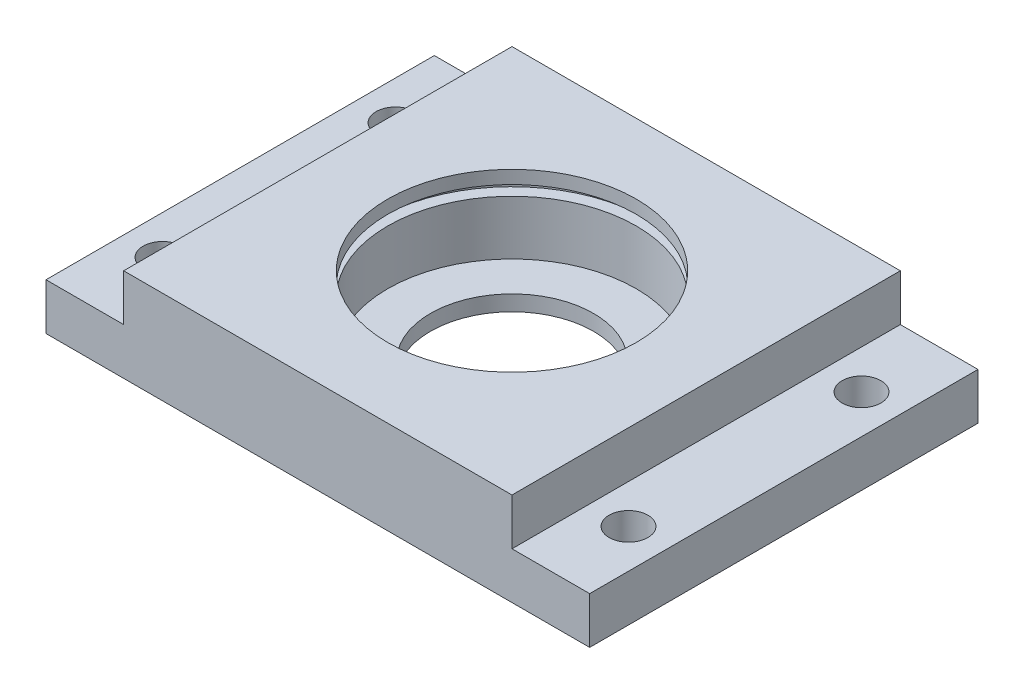
SolidWorks part; units mm, degrees
ref_plane "Front Plane" through (0, 0, 0) normal (0, 0, 1) x (1, 0, 0)
ref_plane "Top Plane" through (0, 0, 0) normal (0, 1, 0) x (1, 0, 0)
ref_plane "Right Plane" through (0, 0, 0) normal (1, 0, 0) x (0, 0, -1)
sketch "Sketch1" plane through (0, 0, 0) normal (0, 1, 0) x (1, 0, 0)
  line L1 (25, 25) -> (-25, 25)
  line L2 (25, 25) -> (25, -25)
  line L3 (25, -25) -> (-25, -25)
  line L4 (-25, 25) -> (-25, -25)
  line L5 (25, 25) -> (-25, -25) construction
  line L6 (25, -25) -> (-25, 25) construction
extrude "Boss-Extrude2" add sketch "Sketch1" along normal blind 12
sketch "Sketch3" plane through (0, 12, 0) normal (0, 1, 0) x (1, 0, 0)
  circle A0 centre (0, 0) radius 16
extrude "Cut-Extrude1" cut sketch "Sketch3" against normal blind 10
sketch "Sketch5" plane through (0, 0, 0) normal (0, 0, 1) x (1, 0, 0)
  line L0 (0, 2) -> (-16, 2) construction
  line L1 (16, 2) -> (-16, 2) construction
  line L2 (0, 2) -> (0, 4.9638) construction
  line L3 (-16, 12) -> (-16, 2) construction
  line L4 (-16, 9) -> (-17.5, 9)
  line L5 (-17.5, 9) -> (-17.5, 10.3)
  line L6 (-17.5, 10.3) -> (-16, 10.3)
  line L7 (-16, 9) -> (-15.7472, 9)
  line L8 (-15.7472, 9) -> (-15.7472, 10.3)
  line L9 (-15.7472, 10.3) -> (-16, 10.3)
revolve "Cut-Revolve1" cut sketch "Sketch5" angle 360 about L2
sketch "Sketch6" plane through (0, 2, 0) normal (0, 1, 0) x (1, 0, 0)
  circle A0 centre (0, 0) radius 10.5
extrude "Cut-Extrude2" cut sketch "Sketch6" against normal blind 10
sketch "Sketch9" plane through (-25, 0, 0) normal (-1, 0, 0) x (0, 0, 1)
  line L0 (25, 12) -> (25, 0) construction
  line L1 (-25, 0) -> (25, 0)
  line L2 (-25, 0) -> (-25, 6)
  line L3 (-25, 6) -> (25, 6)
  line L4 (25, 0) -> (25, 6)
extrude "Boss-Extrude3" add sketch "Sketch9" along normal blind 10
sketch "Sketch11" plane through (25, 0, 0) normal (1, 0, 0) x (0, 0, -1)
  line L1 (25, 0) -> (-25, 0)
  line L2 (25, 0) -> (25, 6)
  line L3 (25, 6) -> (-25, 6)
  line L4 (-25, 0) -> (-25, 6)
extrude "Boss-Extrude4" add sketch "Sketch11" along normal blind 10
sketch "Sketch12" plane through (0, 6, 0) normal (0, 1, 0) x (1, 0, 0)
  line L0 (-30, 25) -> (-30, 15) construction
  line L1 (-35, 25) -> (-25, 25) construction
  line L2 (0, 25) -> (0, 29.5017) construction
  line L3 (25, 25) -> (-25, 25) construction
  line L4 (-35, 0) -> (-40.6275, 0) construction
  line L5 (-35, -25) -> (-35, 25) construction
  circle A0 centre (-30, 15) radius 2.5
  circle A1 centre (-30, -15) radius 2.5
  circle A2 centre (30, -15) radius 2.5
  circle A3 centre (30, 15) radius 2.5
extrude "Cut-Extrude4" cut sketch "Sketch12" against normal blind 10
